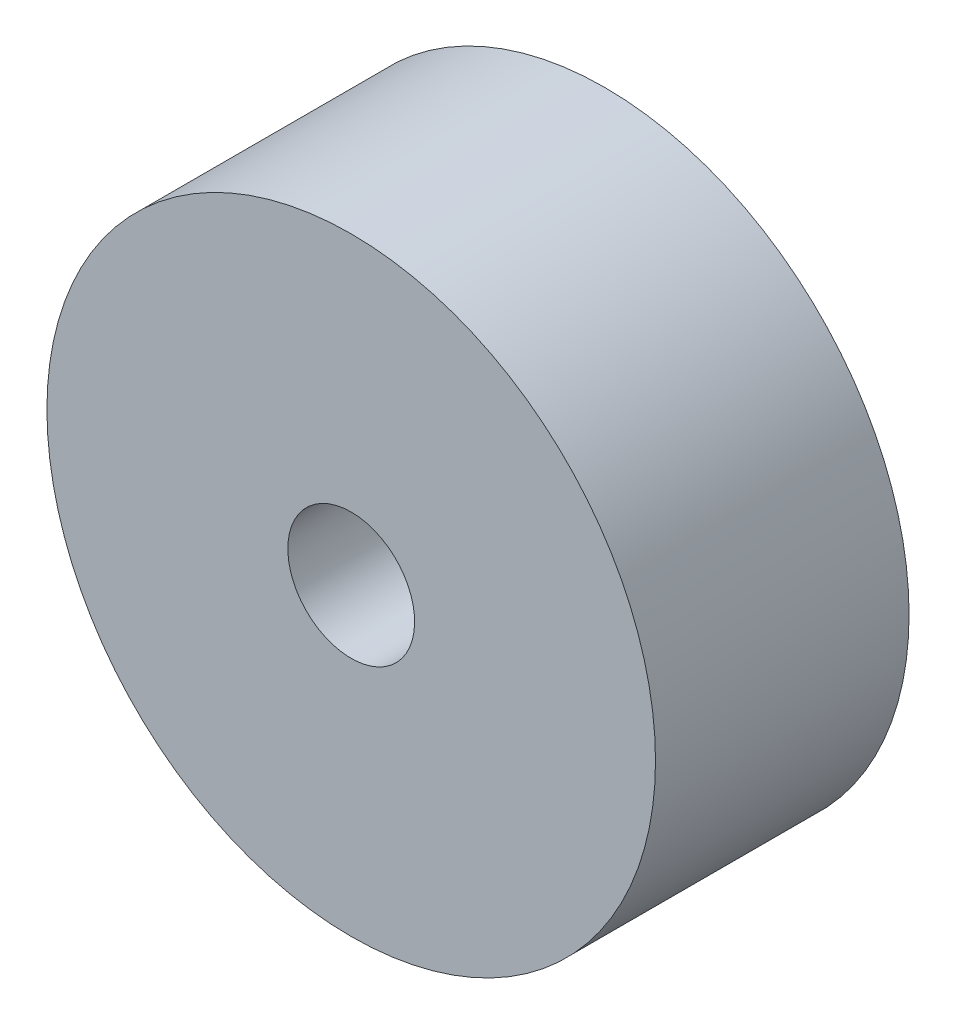
SolidWorks part; units mm, degrees
ref_plane "前视基准面" through (0, 0, 0) normal (0, 0, 1) x (1, 0, 0)
ref_plane "上视基准面" through (0, 0, 0) normal (0, 1, 0) x (1, 0, 0)
ref_plane "右视基准面" through (0, 0, 0) normal (1, 0, 0) x (0, 0, -1)
ref_plane "基准面4" through (0, 0, 0) normal (0, -1, 0) x (1, 0, 0)
sketch "草图1" plane through (0, 0, 0) normal (0, -1, 0) x (1, 0, 0)
  line L0 (0.25, 5) -> (5, 5)
  line L1 (5, 5) -> (5, 10)
  line L2 (5, 10) -> (0.25, 10)
  line L3 (0.25, 10) -> (0.25, 5)
  line L4 (-1, 10) -> (-1, 0) construction
  dimension "D1" = 4.75
  dimension "D2" = 5
  dimension "D3" = 6
revolve "旋转1" add sketch "草图1" angle 360 about L4
scale "缩放比例1" scale about centroid uniform scaling yes scale factor 2
